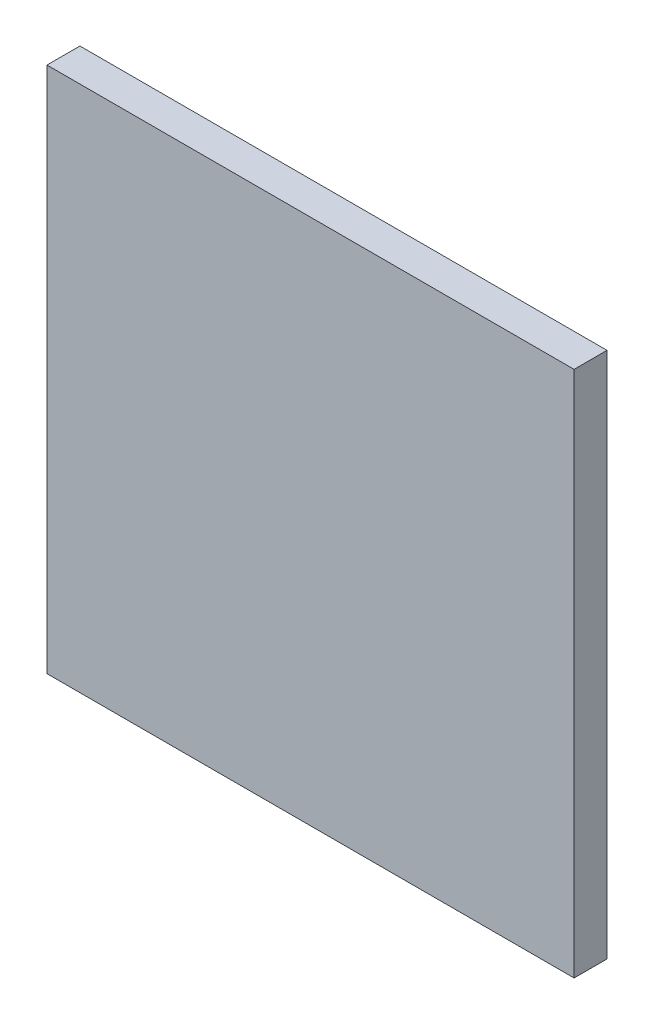
SolidWorks part; units mm, degrees
ref_plane "Plano frontal" through (0, 0, 0) normal (0, 0, 1) x (1, 0, 0)
ref_plane "Plano superior" through (0, 0, 0) normal (0, 1, 0) x (1, 0, 0)
ref_plane "Plano direito" through (0, 0, 0) normal (1, 0, 0) x (0, 0, -1)
sketch "Esboço1" plane through (0, 0, 0) normal (0, 0, 1) x (1, 0, 0)
  line L1 (-221.0169, 159.6) -> (178.9831, 159.6)
  line L2 (-221.0169, 159.6) -> (-221.0169, -240.4)
  line L3 (-221.0169, -240.4) -> (178.9831, -240.4)
  line L4 (178.9831, 159.6) -> (178.9831, -240.4)
  dimension "D1" = 400
  dimension "D2" = 400
extrude "Ressalto-extrusão1" add sketch "Esboço1" along normal blind 25
sketch "Esboço2" plane through (0, 0, 25) normal (0, 0, 1) x (1, 0, 0)
  line L1 (-221.0169, 159.6) -> (-171.0169, 159.6)
  line L2 (-221.0169, 159.6) -> (-221.0169, 109.6)
  line L3 (-221.0169, 109.6) -> (-171.0169, 109.6)
  line L4 (-171.0169, 159.6) -> (-171.0169, 109.6)
  line L9 (-121.0169, 59.6) -> (-71.0169, 59.6)
  line L10 (-121.0169, 59.6) -> (-121.0169, 9.6)
  line L11 (-121.0169, 9.6) -> (-71.0169, 9.6)
  line L12 (-71.0169, 59.6) -> (-71.0169, 9.6)
  line L17 (-21.0169, -40.4) -> (28.9831, -40.4)
  line L18 (-21.0169, -40.4) -> (-21.0169, -90.4)
  line L19 (-21.0169, -90.4) -> (28.9831, -90.4)
  line L20 (28.9831, -40.4) -> (28.9831, -90.4)
  line L25 (79.5518, -140.4) -> (129.5518, -140.4)
  line L26 (79.5518, -140.4) -> (79.5518, -190.4)
  line L27 (79.5518, -190.4) -> (129.5518, -190.4)
  line L28 (129.5518, -140.4) -> (129.5518, -190.4)
  line L41 (-221.0169, 159.6) -> (-221.0169, -240.4) construction
  line L46 (-221.0169, -190.4) -> (-171.0169, -190.4)
  line L47 (-221.0169, -190.4) -> (-221.0169, -140.4)
  line L48 (-221.0169, -140.4) -> (-171.0169, -140.4)
  line L49 (-171.0169, -190.4) -> (-171.0169, -140.4)
  line L50 (-221.0169, -240.4) -> (178.9831, -240.4) construction
  line L51 (-221.0169, -90.4) -> (-171.0169, -90.4)
  line L52 (-221.0169, -90.4) -> (-221.0169, -40.4)
  line L53 (-221.0169, -40.4) -> (-171.0169, -40.4)
  line L54 (-171.0169, -90.4) -> (-171.0169, -40.4)
  line L59 (-121.0169, -190.4) -> (-71.0169, -190.4)
  line L60 (-121.0169, -190.4) -> (-121.0169, -240.4)
  line L61 (-121.0169, -240.4) -> (-71.0169, -240.4)
  line L62 (-71.0169, -190.4) -> (-71.0169, -240.4)
  line L63 (178.9831, 159.6) -> (-221.0169, 159.6) construction
  line L64 (-21.0169, -190.4) -> (28.9831, -190.4)
  line L65 (-21.0169, -190.4) -> (-21.0169, -240.4)
  line L66 (-21.0169, -240.4) -> (28.9831, -240.4)
  line L67 (28.9831, -190.4) -> (28.9831, -240.4)
  line L68 (-122.2043, 159.6) -> (-72.2043, 159.6)
  line L69 (-122.2043, 159.6) -> (-122.2043, 109.6)
  line L70 (-122.2043, 109.6) -> (-72.2043, 109.6)
  line L71 (-72.2043, 159.6) -> (-72.2043, 109.6)
  line L72 (178.9831, -240.4) -> (178.9831, 159.6) construction
  line L73 (-20.7824, 159.6) -> (29.2176, 159.6)
  line L74 (-20.7824, 159.6) -> (-20.7824, 109.6)
  line L75 (-20.7824, 109.6) -> (29.2176, 109.6)
  line L76 (29.2176, 159.6) -> (29.2176, 109.6)
  line L81 (-121.0169, -40.4) -> (-71.0169, -40.4)
  line L82 (178.9831, 59.6) -> (128.9831, 59.6)
  line L83 (178.9831, 59.6) -> (178.9831, 9.6)
  line L84 (178.9831, 9.6) -> (128.9831, 9.6)
  line L85 (128.9831, 59.6) -> (128.9831, 9.6)
  line L86 (178.9831, -40.4) -> (128.9831, -40.4)
  line L87 (178.9831, -40.4) -> (178.9831, -90.4)
  line L88 (178.9831, -90.4) -> (128.9831, -90.4)
  line L89 (128.9831, -40.4) -> (128.9831, -90.4)
  line L90 (78.9831, 59.6) -> (28.9831, 59.6)
  line L91 (78.9831, 59.6) -> (78.9831, 9.6)
  line L92 (78.9831, 9.6) -> (28.9831, 9.6)
  line L93 (28.9831, 59.6) -> (28.9831, 9.6)
  line L94 (-221.0169, 59.6) -> (-171.0169, 59.6)
  line L95 (-221.0169, 59.6) -> (-221.0169, 9.6)
  line L96 (-221.0169, 9.6) -> (-171.0169, 9.6)
  line L97 (-171.0169, 59.6) -> (-171.0169, 9.6)
  line L98 (-121.0169, -40.4) -> (-121.0169, -90.4)
  line L99 (-121.0169, -90.4) -> (-71.0169, -90.4)
  line L100 (-71.0169, -40.4) -> (-71.0169, -90.4)
  line L101 (78.9831, 109.6) -> (128.9831, 109.6)
  line L102 (78.9831, 109.6) -> (78.9831, 159.6)
  line L103 (78.9831, 159.6) -> (128.9831, 159.6)
  line L104 (128.9831, 109.6) -> (128.9831, 159.6)
  point P19 (4.2176, 159.6)
  dimension "D1" = 50
  dimension "D2" = 50
  dimension "D3" = 50
  dimension "D4" = 50
  dimension "D5" = 50
  dimension "D7" = 50
  dimension "D9" = 50
  dimension "D11" = 50
  dimension "D13" = 50
  dimension "D15" = 50
extrude "Ressalto-extrusão3" add sketch "Esboço2" against normal blind 30
sketch "Esboço3" plane through (0, 159.6, 0) normal (0, 1, 0) x (1, 0, 0)
  line L1 (178.9831, 0) -> (-221.0169, 0)
  line L2 (178.9831, 0) -> (178.9831, 5)
  line L3 (178.9831, 5) -> (-221.0169, 5)
  line L4 (-221.0169, 0) -> (-221.0169, 5)
extrude "Corte-extrusão1" cut sketch "Esboço3" against normal through all
